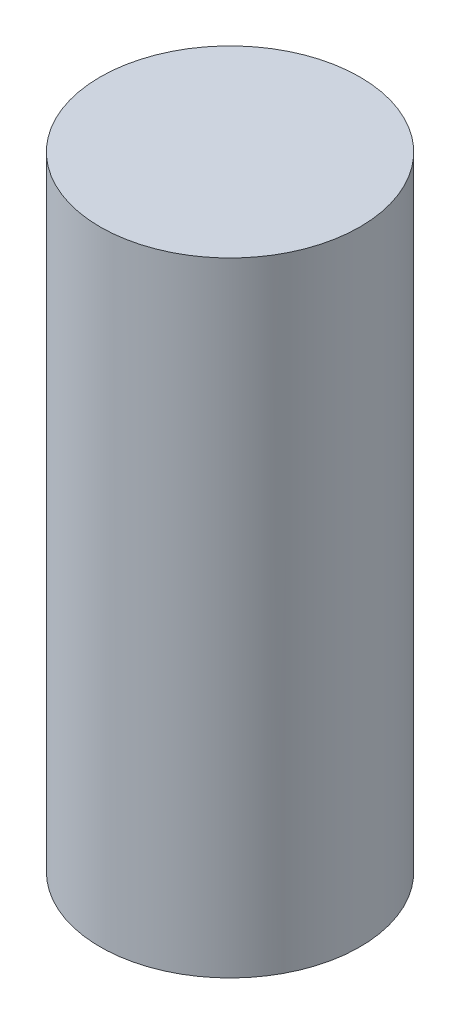
SolidWorks part; units mm, degrees
ref_plane "Front Plane" through (0, 0, 0) normal (0, 0, 1) x (1, 0, 0)
ref_plane "Top Plane" through (0, 0, 0) normal (0, 1, 0) x (1, 0, 0)
ref_plane "Right Plane" through (0, 0, 0) normal (1, 0, 0) x (0, 0, -1)
sketch "Sketch1" plane through (0, 0, 0) normal (0, 1, 0) x (1, 0, 0)
  line L0 (-4, 11) -> (4, 11)
  line L1 (-4, 11) -> (-4, 14.4568)
  line L2 (4, 11) -> (4, 14.4568)
  arc A0 (-4, 14.4568) -> (4, 14.4568) centre (0, 0) ccw
  point P6 (0, 11)
  dimension "D1" = 30
  dimension "D2" = 8
  dimension "D3" = 11
extrude "Boss-Extrude1" add sketch "Sketch1" along normal blind 40
sketch "Sketch2" plane through (0, 40, 0) normal (0, 1, 0) x (1, 0, 0)
  circle A0 centre (0, 0) radius 15
  dimension "D1" = 30
extrude "Boss-Extrude2" add sketch "Sketch2" along normal blind 12
sketch "Sketch3" plane through (0, 0, 0) normal (0, -1, 0) x (1, 0, 0)
  circle A0 centre (0, 0) radius 15
extrude "Boss-Extrude3" add sketch "Sketch3" along normal blind 20
